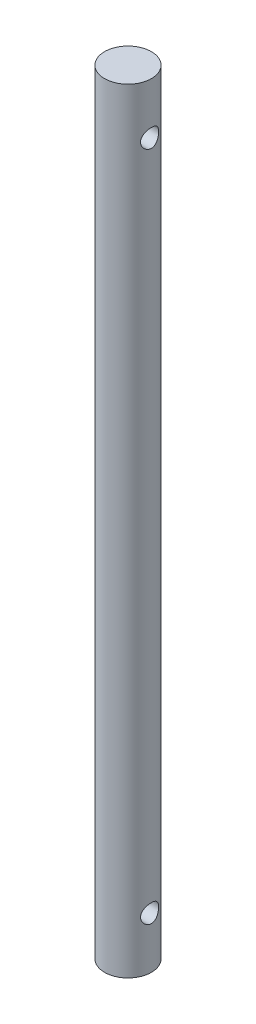
SolidWorks part; units mm, degrees
ref_plane "Front Plane" through (0, 0, 0) normal (0, 0, 1) x (1, 0, 0)
ref_plane "Top Plane" through (0, 0, 0) normal (0, 1, 0) x (1, 0, 0)
ref_plane "Right Plane" through (0, 0, 0) normal (1, 0, 0) x (0, 0, -1)
sketch "Sketch1" plane through (0, 0, 0) normal (0, 1, 0) x (1, 0, 0)
  circle A0 centre (0, 0) radius 3.937
  dimension "D1" = 7.874
extrude "Boss-Extrude1" add sketch "Sketch1" along normal mid plane 130.175
sketch "Sketch2" plane through (0, 0, 0) normal (0, 0, 1) x (1, 0, 0)
  line L0 (3.937, 65.0875) -> (-3.937, 65.0875) construction
  line L1 (-6.6637, 56.4515) -> (8.0603, 56.4515)
  line L2 (-6.6637, 56.4515) -> (-6.6637, 57.9755)
  line L3 (-6.6637, 57.9755) -> (8.0603, 57.9755)
  line L4 (8.0603, 56.4515) -> (8.0603, 57.9755)
  dimension "D1" = 1.524
  dimension "D2" = 8.636
revolve "Cut-Revolve1" cut sketch "Sketch2" angle 360 about L1
sketch "Sketch3" plane through (0, 0, 0) normal (0, 0, 1) x (1, 0, 0)
  line L0 (-3.937, -65.0875) -> (3.937, -65.0875) construction
  line L1 (-7.1714, -57.9755) -> (7.3219, -57.9755)
  line L2 (-7.1714, -57.9755) -> (-7.1714, -56.4515)
  line L3 (-7.1714, -56.4515) -> (7.3219, -56.4515)
  line L4 (7.3219, -57.9755) -> (7.3219, -56.4515)
  dimension "D1" = 1.524
  dimension "D2" = 8.636
revolve "Cut-Revolve2" cut sketch "Sketch3" angle 360 about L3
